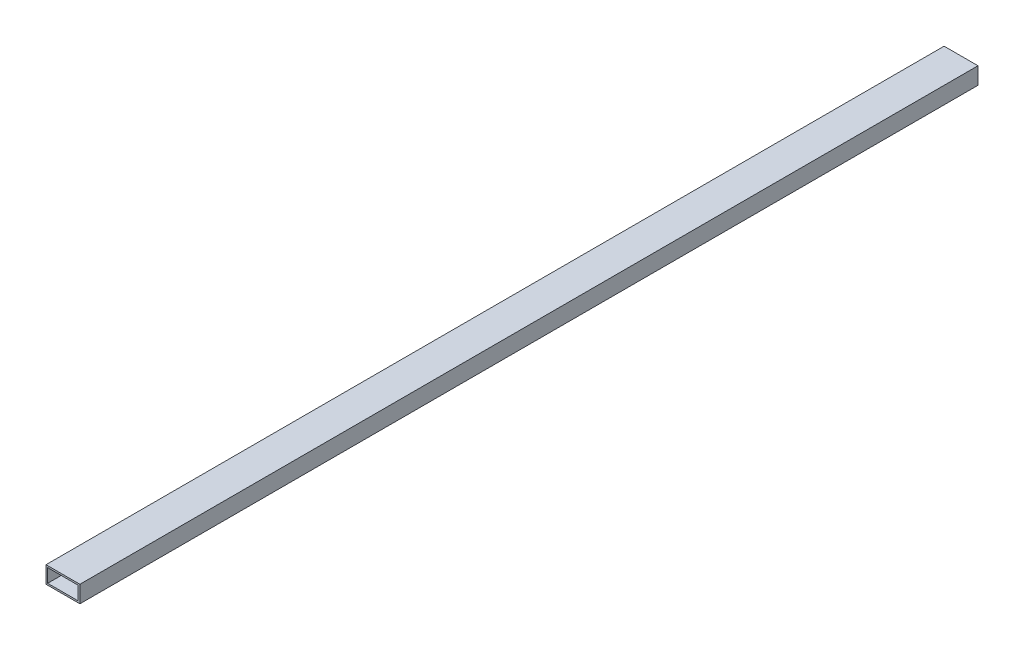
SolidWorks part; units mm, degrees
material "2024-O"
ref_plane "Alzado" through (0, 0, 0) normal (0, 0, 1) x (1, 0, 0)
ref_plane "Planta" through (0, 0, 0) normal (0, 1, 0) x (1, 0, 0)
ref_plane "Vista lateral" through (0, 0, 0) normal (1, 0, 0) x (0, 0, -1)
sketch "Croquis1" plane through (0, 0, 0) normal (0, 0, 1) x (1, 0, 0)
  line L1 (20, -10) -> (-20, -10)
  line L2 (20, -10) -> (20, 10)
  line L3 (20, 10) -> (-20, 10)
  line L4 (-20, -10) -> (-20, 10)
  line L5 (20, -10) -> (-20, 10) construction
  line L6 (20, 10) -> (-20, -10) construction
  point P0 (0, 0)
  dimension "D1" = 40
  dimension "D2" = 20
extrude "Extruir-Lámina1" add sketch "Croquis1" along normal blind 1060 thin
